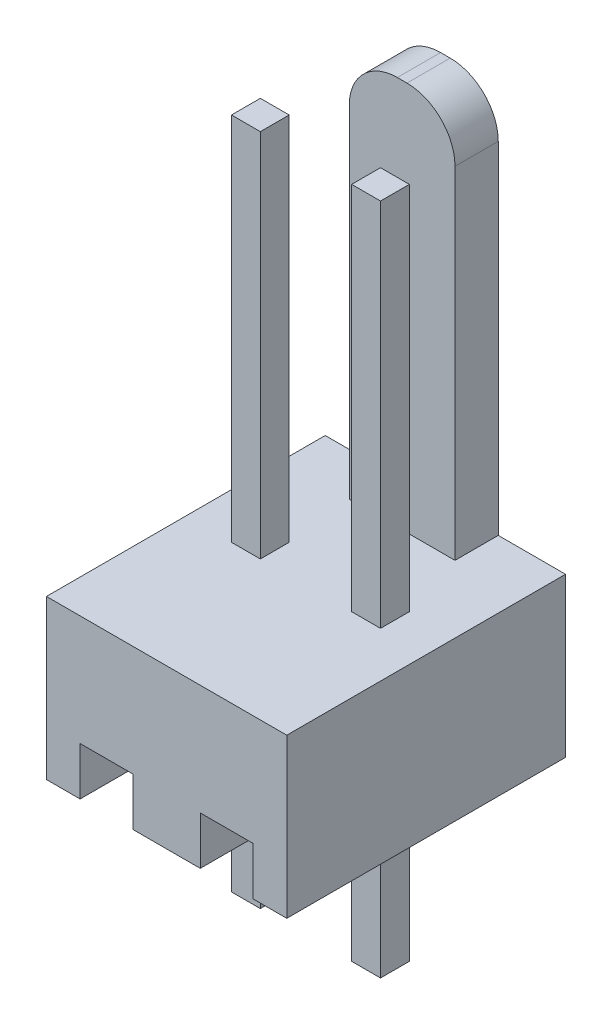
SolidWorks part; units mm, degrees
ref_plane "Alzado" through (0, 0, 0) normal (0, 0, 1) x (1, 0, 0)
ref_plane "Planta" through (0, 0, 0) normal (0, 1, 0) x (1, 0, 0)
ref_plane "Vista lateral" through (0, 0, 0) normal (1, 0, 0) x (0, 0, -1)
sketch "Croquis1" plane through (0, 0, 0) normal (0, 1, 0) x (1, 0, 0)
  line L1 (-2.5, 2.9) -> (2.5, 2.9)
  line L2 (-2.5, 2.9) -> (-2.5, -2.9)
  line L3 (-2.5, -2.9) -> (2.5, -2.9)
  line L4 (2.5, 2.9) -> (2.5, -2.9)
  line L5 (-2.5, 2.9) -> (2.5, -2.9) construction
  line L6 (-2.5, -2.9) -> (2.5, 2.9) construction
  point P0 (0, 0)
extrude "Saliente-Extruir1" add sketch "Croquis1" along normal blind 3.3
sketch "Croquis4" plane through (0, 0, 0) normal (0, -1, 0) x (1, 0, 0)
  line L0 (-2.5, 2.9) -> (-1.8, 2.9) construction
  line L1 (-2.5, 2.9) -> (2.5, 2.9) construction
  line L2 (-1.8, 2.9) -> (-0.7, 2.9) construction
  line L3 (-0.7, 2.9) -> (0.7, 2.9) construction
  line L4 (0.7, 2.9) -> (1.8, 2.9) construction
  line L5 (1.8, 2.9) -> (2.5, 2.9) construction
  line L6 (-1.8, 2.9) -> (-1.8, -2.9)
  line L7 (2.5, -2.9) -> (-2.5, -2.9) construction
  line L8 (-1.8, -2.9) -> (-0.7, -2.9)
  line L9 (-0.7, -2.9) -> (-0.7, 2.9)
  line L10 (-0.7, 2.9) -> (-1.8, 2.9)
  line L11 (0.7, 2.9) -> (1.8, 2.9)
  line L12 (1.8, 2.9) -> (1.8, -2.9)
  line L13 (1.8, -2.9) -> (0.7, -2.9)
  line L14 (0.7, -2.9) -> (0.7, 2.9)
  dimension "D1" = 0.7
  dimension "D2" = 1.1
  dimension "D3" = 1.4
  dimension "D4" = 1.1
  dimension "D5" = 0.7
extrude "Cortar-Extruir1" cut sketch "Croquis4" against normal blind 1
sketch "Croquis5" plane through (0, 3.3, 0) normal (0, 1, 0) x (1, 0, 0)
  line L0 (-2.5, 2.9) -> (-1.1, 2.9) construction
  line L1 (2.5, 2.9) -> (-2.5, 2.9) construction
  line L2 (-1.1, 2.9) -> (1.1, 2.9) construction
  line L3 (1.1, 2.9) -> (2.5, 2.9) construction
  line L4 (-1.1, 2.9) -> (1.1, 2.9)
  line L5 (1.1, 2.9) -> (1.1, 2)
  line L6 (1.1, 2) -> (-1.1, 2)
  line L7 (-1.1, 2) -> (-1.1, 2.9)
  dimension "D1" = 2.2
  dimension "D2" = 1.4
  dimension "D3" = 1.4
  dimension "D4" = 0.9
extrude "Saliente-Extruir2" add sketch "Croquis5" along normal blind 8.1
fillet "Redondeo4" radius 1 2 edges at (-1.1, 11.4, -2.45)
fillet "Redondeo5" radius 1 2 edges at (1.1, 11.4, -2.45)
sketch "Croquis6" plane through (0, 1, 0) normal (0, -1, 0) x (1, 0, 0)
  line L0 (1.8, 2.9) -> (1.8, -0.6) construction
  line L1 (1.8, -2.9) -> (1.8, 2.9) construction
  line L2 (1.8, -0.6) -> (0.7, -0.6) construction
  line L3 (0.7, 2.9) -> (0.7, -2.9) construction
  line L4 (0.7, -0.6) -> (0.95, -0.6) construction
  line L5 (0.95, -0.6) -> (1.55, -0.6) construction
  line L7 (1.55, -0.6) -> (1.8, -0.6) construction
  line L8 (1.55, -0.6) -> (0.95, -0.6)
  line L9 (1.55, -0.6) -> (1.55, 0)
  line L10 (0.95, -0.6) -> (0.95, 0)
  line L11 (1.55, 0) -> (0.95, 0)
  line L12 (0.7, -0.6) -> (-0.7, -0.6) construction
  line L13 (-0.7, -2.9) -> (-0.7, 2.9) construction
  line L14 (-0.7, -0.6) -> (-0.95, -0.6) construction
  line L15 (-0.95, -0.6) -> (-1.55, -0.6) construction
  line L16 (-1.55, -0.6) -> (-1.8, -0.6) construction
  line L17 (-1.8, 2.9) -> (-1.8, -2.9) construction
  line L18 (-0.95, -0.6) -> (-1.55, -0.6)
  line L19 (-0.95, -0.6) -> (-0.95, 0)
  line L20 (-1.55, -0.6) -> (-1.55, 0)
  line L21 (-0.95, 0) -> (-1.55, 0)
  dimension "D2" = 1.1
  dimension "D1" = 3.5
  dimension "D3" = 0.6
  dimension "D4" = 0.25
  dimension "D5" = 0.25
  dimension "D6" = 0.6
  dimension "D7" = 0.25
  dimension "D8" = 0.6
  dimension "D9" = 0.25
  dimension "D10" = 0.6
extrude "Saliente-Extruir3" add sketch "Croquis6" along normal blind 4 and the other way blind 10
